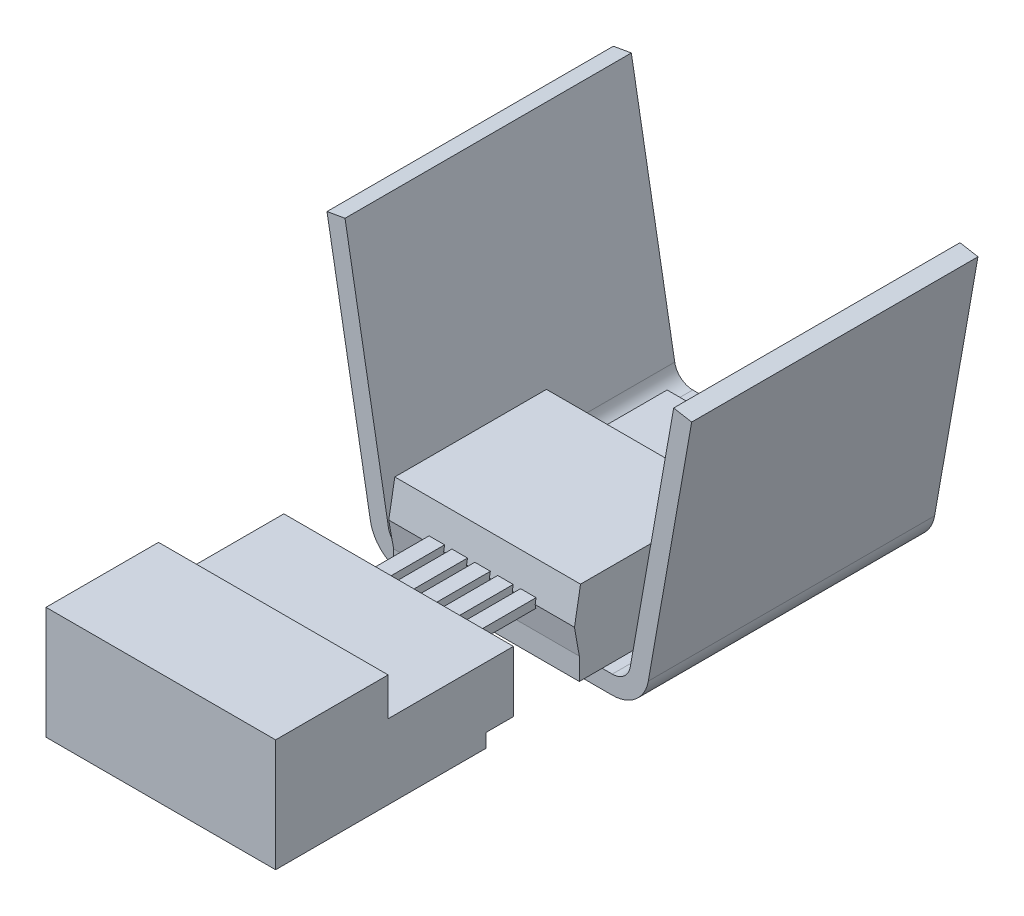
SolidWorks part; units mm, degrees
ref_plane "Front Plane" through (0, 0, 0) normal (0, 0, 1) x (1, 0, 0)
ref_plane "Top Plane" through (0, 0, 0) normal (0, 1, 0) x (1, 0, 0)
ref_plane "Right Plane" through (0, 0, 0) normal (1, 0, 0) x (0, 0, -1)
sketch "Sketch1" plane through (0, 0, 0) normal (0, 1, 0) x (1, 0, 0)
  line L1 (-5.1562, 2.794) -> (5.1562, 2.794)
  line L2 (-5.1562, 2.794) -> (-5.1562, -12.3952)
  line L3 (-5.1562, -12.3952) -> (5.1562, -12.3952)
  line L4 (5.1562, 2.794) -> (5.1562, -12.3952)
  circle A0 centre (0, 0) radius 1.8669
  point P7 (0, 2.794)
  dimension "D2" = 3.7338
  dimension "D1" = 2.794
  dimension "D3" = 10.3124
  dimension "D4" = 15.1892
extrude "Boss-Extrude1" add sketch "Sketch1" along normal blind 1.27
sketch "Sketch2" plane through (0, 0, 0) normal (1, 0, 0) x (0, 0, -1)
  line L0 (-3.302, 1.2192) -> (-3.9066, 4.6482)
  line L1 (-3.9066, 4.6482) -> (-12.328, 4.6482)
  line L2 (-12.328, 4.6482) -> (-12.6639, 2.7432)
  line L3 (-12.6639, 2.7432) -> (-12.3952, 1.2192)
  line L4 (-12.3952, 1.2192) -> (-3.302, 1.2192)
  dimension "D1" = 3.302
  dimension "D2" = 1.2192
  dimension "D3" = 4.6482
  dimension "D4" = 80
  dimension "D5" = 80
  dimension "D6" = 2.7432
extrude "Boss-Extrude2" add sketch "Sketch2" along normal up to surface and the other way up to surface up to face at (5.1562, 0.635, 4.8006) other way up to face at (-5.1562, 0.635, 4.8006)
ref_plane "Plane1" through (2.54, 0, 0) normal (1, 0, 0) x (0, 0, -1)
sketch "Sketch3" plane through (2.54, 0, 0) normal (1, 0, 0) x (0, 0, -1)
  line L0 (-11.1252, 2.54) -> (-18.7452, 2.54)
  line L1 (-18.7807, 2.5406) -> (-25.0506, 2.7596)
  line L2 (-25.0506, 2.7596) -> (-25.0329, 3.2673)
  line L3 (-25.0329, 3.2673) -> (-18.7629, 3.0483)
  line L4 (-18.7452, 3.048) -> (-11.1252, 3.048)
  line L5 (-11.1252, 3.048) -> (-11.1252, 2.54)
  line L6 (-26.2128, -5.9497) -> (-19.939, -5.9497) construction
  line L7 (-19.939, -5.9497) -> (-18.7452, -5.9497) construction
  line L8 (-18.7452, -5.9497) -> (-12.3952, -5.9497) construction
  arc A0 (-18.7629, 3.0483) -> (-18.7452, 3.048) centre (-18.7452, 3.556) ccw
  arc A1 (-18.7452, 2.54) -> (-18.7807, 2.5406) centre (-18.7452, 3.556) cw
  arc A2 (-18.7452, 2.794) -> (-19.3134, 3.0483) centre (-18.7452, 3.556) cw construction
  point P16 (-11.1252, 2.794)
  dimension "D2" = 0.508
  dimension "D3" = 6.2738
  dimension "D7" = 0.6413
  dimension "D1" = 0.508
  dimension "D4" = 13.8176
  dimension "D5" = 2.54
  dimension "D6" = 1.27
  dimension "D8" = 1.1938
  dimension "D9" = 6.2738
  dimension "D11" = 2
extrude "Boss-Extrude3" add sketch "Sketch3" along normal mid plane 0.8636
pattern_linear "LPattern1" count 5 spacing 1.27 along (-1, 0, 0) of "Boss-Extrude3"
sketch "Sketch4" plane through (0, 0, 0) normal (1, 0, 0) x (0, 0, -1)
  line L0 (-18.796, 0.5969) -> (-30.48, 0.5969)
  line L1 (-30.48, 0.5969) -> (-30.48, 6.8453)
  line L2 (-30.48, 6.8453) -> (-24.2316, 6.8453)
  line L3 (-24.2316, 6.8453) -> (-24.2316, 4.7371)
  line L4 (-24.2316, 4.7371) -> (-17.272, 4.7371)
  line L5 (-17.272, 4.7371) -> (-17.272, 1.3589)
  line L6 (-17.272, 4.7371) -> (-17.272, 8.9747) construction
  line L7 (-18.796, 0.5969) -> (-18.796, 1.3589)
  line L8 (-18.796, 1.3589) -> (-17.272, 1.3589)
  point P7 (-17.272, 3.048)
  dimension "D1" = 90
  dimension "D2" = 4.1402
  dimension "D3" = 6.2484
  dimension "D4" = 13.208
  dimension "D5" = 6.2484
  dimension "D6" = 0.762
  dimension "D7" = 1.524
  dimension "D8" = 3.048
  dimension "D9" = 17.272
extrude "Boss-Extrude4" add sketch "Sketch4" along normal mid plane 12.7508
sketch "Sketch5" plane through (0, 0, 0) normal (0, 0, 1) x (1, 0, 0)
  line L0 (5.715, 0) -> (-5.715, 0)
  line L1 (-6.7156, 0.8396) -> (-9.1247, 14.5027)
  line L2 (-9.1247, 14.5027) -> (-10.1253, 14.3262)
  line L3 (-10.1253, 14.3262) -> (-7.7161, 0.6631)
  line L4 (-5.715, -1.016) -> (5.715, -1.016)
  line L5 (0, -3.6318) -> (0, -8.7151) construction
  line L6 (10.1253, 14.3262) -> (7.7161, 0.6631)
  line L7 (9.1247, 14.5027) -> (10.1253, 14.3262)
  line L8 (6.7156, 0.8396) -> (9.1247, 14.5027)
  arc A0 (-5.715, 0) -> (-6.7156, 0.8396) centre (-5.715, 1.016) cw
  arc A1 (-7.7161, 0.6631) -> (-5.715, -1.016) centre (-5.715, 1.016) ccw
  arc A2 (7.7161, 0.6631) -> (5.715, -1.016) centre (5.715, 1.016) cw
  arc A3 (5.715, 0) -> (6.7156, 0.8396) centre (5.715, 1.016) ccw
  dimension "D2" = 1.016
  dimension "D1" = 1.016
  dimension "D3" = 100
  dimension "D4" = 11.43
  dimension "D5" = 15.875
extrude "Boss-Extrude5" add sketch "Sketch5" along normal blind 11.1252 and the other way blind 4.7752
